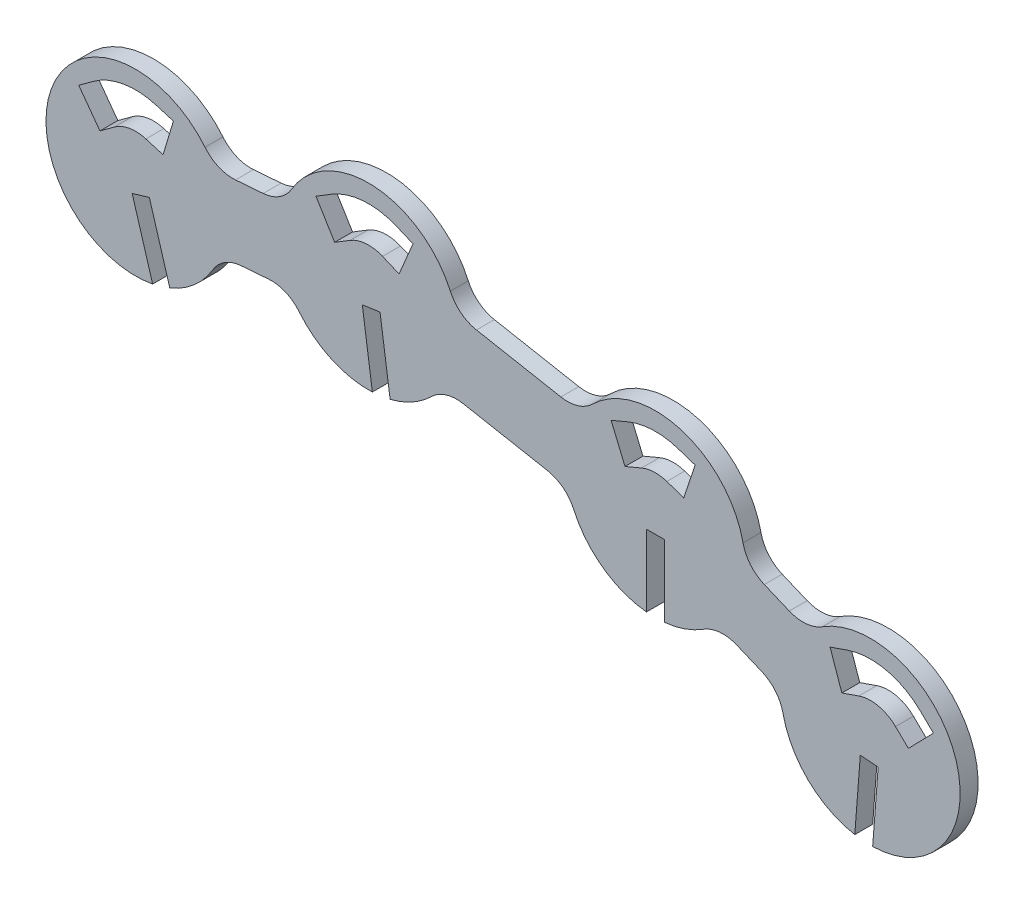
SolidWorks part; units mm, degrees
ref_plane "Front Plane" through (0, 0, 0) normal (0, 0, 1) x (1, 0, 0)
ref_plane "Top Plane" through (0, 0, 0) normal (0, 1, 0) x (1, 0, 0)
ref_plane "Right Plane" through (0, 0, 0) normal (1, 0, 0) x (0, 0, -1)
sketch "Sketch1" plane through (0, 0, 0) normal (0, 0, 1) x (1, 0, 0)
  line L0 (-51.2912, 76.2) -> (64262.6532, 76.2) construction
  line L5 (7.4715, 147.6375) -> (64321.4159, 147.6375) construction
  line L6 (118.3446, 158.75) -> (64432.2889, 158.75) construction
  line L7 (275.7842, 163.5125) -> (64589.7286, 163.5125) construction
  line L8 (55.5625, 439.4786) -> (55.5625, -63874.4658) construction
  line L9 (111.125, 452.7834) -> (111.125, -63861.161) construction
  line L10 (119.0625, 453.8921) -> (119.0625, -63860.0523) construction
  line L11 (99.4961, 73.025) -> (64413.4405, 73.025) construction
  line L12 (93.9525, 3.175) -> (64407.8969, 3.175) construction
  line L13 (33.9504, 0) -> (64347.8947, 0) construction
  line L14 (-39.0951, -3.175) -> (64274.8492, -3.175) construction
  line L15 (-110.0539, -73.025) -> (64203.8905, -73.025) construction
  line L16 (198.1731, 65.0875) -> (64512.1175, 65.0875) construction
  line L17 (201.4993, 77.7875) -> (64515.4437, 77.7875) construction
  line L18 (276.893, 155.575) -> (64590.8373, 155.575) construction
  line L19 (351.1779, 168.275) -> (64665.1223, 168.275) construction
  line L20 (107.95, 410.6516) -> (107.95, -63903.2928) construction
  line L21 (95.25, 453.8921) -> (95.25, -63860.0523) construction
  line L22 (87.3125, 480.5016) -> (87.3125, -63833.4428) construction
  line L23 (34.925, 470.523) -> (34.925, -63843.4213) construction
  line L24 (0, 558.1122) -> (0, -63755.8322) construction
  line L25 (127, 731.8887) -> (127, -63582.0557) construction
  line L26 (133.35, 785.5707) -> (133.35, -63528.3737) construction
  line L27 (146.05, 782.952) -> (146.05, -63530.9923) construction
  line L28 (147.6375, 792.1173) -> (147.6375, -63521.8271) construction
  line L29 (152.4, 819.6129) -> (152.4, -63494.3315) construction
  line L30 (161.925, 852.3458) -> (161.925, -63461.5986) construction
  line L31 (206.375, 822.2315) -> (206.375, -63491.7129) construction
  line L32 (-303.6442, 138.1125) -> (49696.3558, 138.1125) construction
  line L33 (-178.9515, 120.65) -> (49821.0485, 120.65) construction
  point P60 (111.125, -3.175)
  point P61 (119.0625, 0)
  point P62 (133.35, 3.175)
  point P63 (147.6375, 3.175)
  point P64 (107.95, 77.7875)
  point P65 (133.35, 73.025)
  point P66 (152.4, 65.0875)
  point P67 (87.3125, 76.2)
  point P68 (34.925, 147.6375)
  point P69 (55.5625, 163.5125)
  point P70 (111.125, 155.575)
  point P71 (95.25, 163.5125)
  point P72 (127, 138.1125)
  point P73 (146.05, 168.275)
  point P74 (161.925, 158.75)
  point P77 (206.375, 120.65)
  dimension "D1" = 69.85
  dimension "D2" = 73.025
  dimension "D3" = 76.2
  dimension "D4" = 138.1125
  dimension "D5" = 146.05
  dimension "D6" = 150.8125
  dimension "D7" = 149.225
  dimension "D8" = 211.1375
  dimension "D9" = 220.6625
  dimension "D10" = 228.6
  dimension "D11" = 231.775
  dimension "D12" = 236.5375
  dimension "D13" = 241.3
  dimension "D14" = 34.925
  dimension "D15" = 55.5625
  dimension "D16" = 87.3125
  dimension "D17" = 95.25
  dimension "D18" = 107.95
  dimension "D19" = 111.125
  dimension "D20" = 119.0625
  dimension "D21" = 127
  dimension "D22" = 133.35
  dimension "D23" = 146.05
  dimension "D24" = 147.6375
  dimension "D25" = 152.4
  dimension "D26" = 161.925
  dimension "D27" = 206.375
  dimension "D28" = 193.675
sketch "Sketch2" plane through (0, 0, 0) normal (0, 0, 1) x (1, 0, 0)
  line L0 (111.125, -3.175) -> (87.3125, 76.2)
  line L1 (119.0625, 0) -> (107.95, 77.7875)
  line L2 (133.35, 3.175) -> (133.35, 73.025)
  line L3 (147.6375, 3.175) -> (152.4, 65.0875)
  line L4 (152.4, 65.0875) -> (206.375, 120.65)
  line L5 (152.4, 65.0875) -> (127, 138.1125)
  line L6 (133.35, 73.025) -> (161.925, 158.75)
  line L7 (-199881.6554, 158.75) -> (264432.2889, 158.75) construction
  line L8 (133.35, 73.025) -> (95.25, 163.5125)
  line L9 (107.95, 77.7875) -> (146.05, 168.275)
  line L10 (107.95, 77.7875) -> (55.5625, 163.5125)
  line L11 (87.3125, 76.2) -> (111.125, 155.575)
  line L12 (87.3125, 76.2) -> (34.925, 147.6375)
sketch "Sketch4" plane through (0, 0, 0) normal (0, 0, 1) x (1, 0, 0)
  line L0 (87.3125, 76.2) -> (107.95, 77.7875) construction
  line L1 (107.95, 77.7875) -> (133.35, 73.025) construction
  line L2 (133.35, 73.025) -> (152.4, 65.0875) construction
  line L3 (94.8094, 73.5923) -> (100.9401, 74.0639)
  line L4 (114.5151, 73.3262) -> (125.6146, 71.2451)
  line L5 (138.8441, 67.2962) -> (146.05, 64.2937)
  line L6 (111.125, -3.175) -> (87.3125, 76.2) construction
  line L7 (107.1642, 77.6752) -> (108.2868, 69.8175) construction
  line L8 (141.2864, 73.1578) -> (146.9059, 70.8163)
  line L9 (87.069, 79.3656) -> (108.1238, 80.9852) construction
  line L10 (87.556, 73.0344) -> (107.7762, 74.5898) construction
  line L11 (134.2631, 76.0841) -> (153.6212, 68.0183) construction
  line L12 (132.4369, 69.9659) -> (151.1788, 62.1567) construction
  line L13 (146.05, 200782.952) -> (146.05, -263530.9923) construction
  line L14 (108.1238, 80.9852) -> (134.2631, 76.0841) construction
  line L15 (107.7762, 74.5898) -> (132.4369, 69.9659) construction
  line L16 (108.7358, 77.8998) -> (109.8583, 70.042) construction
  line L17 (107.3887, 76.1037) -> (108.9603, 76.3282)
  line L18 (94.3224, 79.9236) -> (100.4531, 80.3952)
  line L19 (115.6854, 79.5674) -> (126.7849, 77.4863)
  line L20 (132.5563, 73.025) -> (132.5563, 65.0875) construction
  line L21 (134.1438, 73.025) -> (134.1438, 65.0875) construction
  line L22 (132.5563, 71.4773) -> (134.1438, 71.4773)
  line L23 (151.4899, 63.6052) -> (151.0029, 57.2739)
  line L24 (153.0727, 63.4835) -> (152.5857, 57.1522)
  line L25 (151.4899, 63.6052) -> (153.0727, 63.4835)
  line L26 (152.4, 65.0875) -> (206.375, 120.65) construction
  line L27 (152.4, 65.0875) -> (127, 138.1125) construction
  line L28 (133.35, 73.025) -> (161.925, 158.75) construction
  line L29 (133.35, 73.025) -> (95.25, 163.5125) construction
  line L30 (87.3125, 76.2) -> (89.5933, 68.5973)
  line L31 (107.95, 77.7875) -> (109.0725, 69.9298)
  line L32 (119.0625, 0) -> (107.95, 77.7875) construction
  line L33 (133.35, 73.025) -> (133.35, 65.0875)
  line L34 (152.4, 65.0875) -> (151.7912, 57.1734)
  line L35 (147.6375, 3.175) -> (152.4, 65.0875) construction
  line L36 (87.0084, 74.4514) -> (88.8216, 68.4073)
  line L37 (107.3887, 76.1037) -> (108.2811, 69.8569)
  line L38 (132.5563, 71.4773) -> (132.5563, 65.1273)
  line L39 (107.95, 77.7875) -> (146.05, 168.275) construction
  line L40 (88.5289, 74.9075) -> (90.3422, 68.8634)
  line L41 (108.9603, 76.3282) -> (109.8527, 70.0814)
  line L42 (134.1438, 71.4773) -> (134.1438, 65.1273)
  line L43 (107.95, 77.7875) -> (55.5625, 163.5125) construction
  line L44 (88.0728, 76.4281) -> (90.3536, 68.8253) construction
  line L45 (86.5522, 75.9719) -> (88.833, 68.3692) construction
  line L46 (87.0084, 74.4514) -> (88.5289, 74.9075)
  line L47 (87.3125, 76.2) -> (111.125, 155.575) construction
  line L48 (87.3125, 76.2) -> (34.925, 147.6375) construction
  line L49 (83.5573, 81.3207) -> (85.4349, 78.7603)
  line L50 (88.2248, 79.2411) -> (89.1372, 82.2822)
  line L51 (106.2944, 80.4967) -> (104.6388, 83.2058)
  line L52 (109.1821, 80.7137) -> (110.4142, 83.6399)
  line L53 (132.1179, 75.9512) -> (130.8858, 78.8774)
  line L54 (134.354, 76.0371) -> (135.358, 79.0491)
  line L55 (151.3569, 68.0863) -> (150.3139, 71.0851)
  line L56 (154.6123, 67.3649) -> (156.8246, 69.6422)
  line L57 (82.2772, 80.3819) -> (84.1548, 77.8215)
  line L58 (89.7454, 78.7849) -> (90.6577, 81.826)
  line L59 (110.6452, 80.0977) -> (111.8773, 83.0238)
  line L60 (135.8601, 75.5351) -> (136.8641, 78.5471)
  line L61 (155.751, 66.2587) -> (157.9633, 68.5361)
  line L62 (149.8576, 67.5648) -> (148.8145, 70.5635)
  line L63 (130.6548, 75.3352) -> (129.4227, 78.2613)
  line L64 (104.9398, 79.6689) -> (103.2842, 82.378)
  line L65 (83.5573, 81.3207) -> (82.2772, 80.3819)
  line L66 (156.8246, 69.6422) -> (157.9633, 68.5361)
  line L67 (84.1548, 77.8215) -> (85.4349, 78.7603)
  line L68 (88.2248, 79.2411) -> (89.7454, 78.7849)
  line L69 (154.6123, 67.3649) -> (155.751, 66.2587)
  line L70 (149.8576, 67.5648) -> (151.3569, 68.0863)
  line L71 (148.8145, 70.5635) -> (150.3139, 71.0851)
  line L72 (129.4227, 78.2613) -> (130.8858, 78.8774)
  line L73 (130.6548, 75.3352) -> (132.1179, 75.9512)
  line L74 (135.358, 79.0491) -> (136.8641, 78.5471)
  line L75 (134.354, 76.0371) -> (135.8601, 75.5351)
  line L76 (89.1372, 82.2822) -> (90.6577, 81.826)
  line L77 (103.2842, 82.378) -> (104.6388, 83.2058)
  line L78 (104.9398, 79.6689) -> (106.2944, 80.4967)
  line L79 (110.4142, 83.6399) -> (111.8773, 83.0238)
  line L80 (109.1821, 80.7137) -> (110.6452, 80.0977)
  circle A0 centre (87.3125, 76.2) radius 7.9375
  circle A1 centre (107.95, 77.7875) radius 7.9375
  circle A2 centre (133.35, 73.025) radius 7.9375
  circle A3 centre (152.4, 65.0875) radius 7.9375
  circle A16 centre (152.4, 65.0875) radius 4.7625 construction
  circle A17 centre (133.35, 73.025) radius 4.7625 construction
  circle A18 centre (107.95, 77.7875) radius 4.7625 construction
  circle A19 centre (87.3125, 76.2) radius 4.7625 construction
  circle A20 centre (155.7184, 68.5035) radius 1.5875
  circle A21 centre (150.8354, 69.5857) radius 1.5875
  circle A22 centre (134.856, 77.5431) radius 1.5875
  circle A23 centre (131.5019, 77.4143) radius 1.5875
  circle A24 centre (109.7981, 82.1768) radius 1.5875
  circle A25 centre (105.4666, 81.8513) radius 1.5875
  circle A26 centre (88.681, 80.7616) radius 1.5875
  circle A27 centre (84.4961, 80.0405) radius 1.5875
  arc A28 (154.6123, 67.3649) -> (151.3569, 68.0863) centre (152.4, 65.0875) ccw
  arc A29 (156.8246, 69.6422) -> (150.3139, 71.0851) centre (152.4, 65.0875) ccw
  arc A30 (134.354, 76.0371) -> (132.1179, 75.9512) centre (133.35, 73.025) ccw
  arc A31 (130.8858, 78.8774) -> (135.358, 79.0491) centre (133.35, 73.025) cw
  arc A32 (109.1821, 80.7137) -> (106.2944, 80.4967) centre (107.95, 77.7875) ccw
  arc A33 (110.4142, 83.6399) -> (104.6388, 83.2058) centre (107.95, 77.7875) ccw
  arc A34 (88.2248, 79.2411) -> (85.4349, 78.7603) centre (87.3125, 76.2) ccw
  arc A35 (89.1372, 82.2822) -> (83.5573, 81.3207) centre (87.3125, 76.2) ccw
  dimension "D1" = 15.875
  dimension "D15" = 9.525
  dimension "D16" = 3.175
  dimension "D17" = 1.5875
  dimension "D2" = 3.175
  dimension "D4" = 3.175
  dimension "D5" = 3.175
  dimension "D7" = 0.7937
  dimension "D9" = 6.35
  dimension "D10" = 6.35
  dimension "D11" = 6.35
  dimension "D12" = 0.7937
  dimension "D14" = 6.35
  dimension "D13" = 0.7937
  dimension "D3" = 3.175
  dimension "D8" = 0.7937
  dimension "D18" = 1.5875
extrude "Boss-Extrude1" add sketch "Sketch4" along normal blind 1.5875
fillet "Fillet1" radius 3.175 12 edges at (94.8094, 73.5923, 0.7937) (100.9401, 74.0639, 0.7937) (144.4636, 64.9547, 0.7937) (138.8441, 67.2962, 0.7937) (125.6146, 71.2451, 0.7937) (114.5151, 73.3262, 0.7937) (141.2864, 73.1578, 0.7937) (115.6854, 79.5674, 0.7937) (126.7849, 77.4863, 0.7937) (146.9059, 70.8163, 0.7937) (100.4531, 80.3952, 0.7937) (94.3224, 79.9236, 0.7937)
